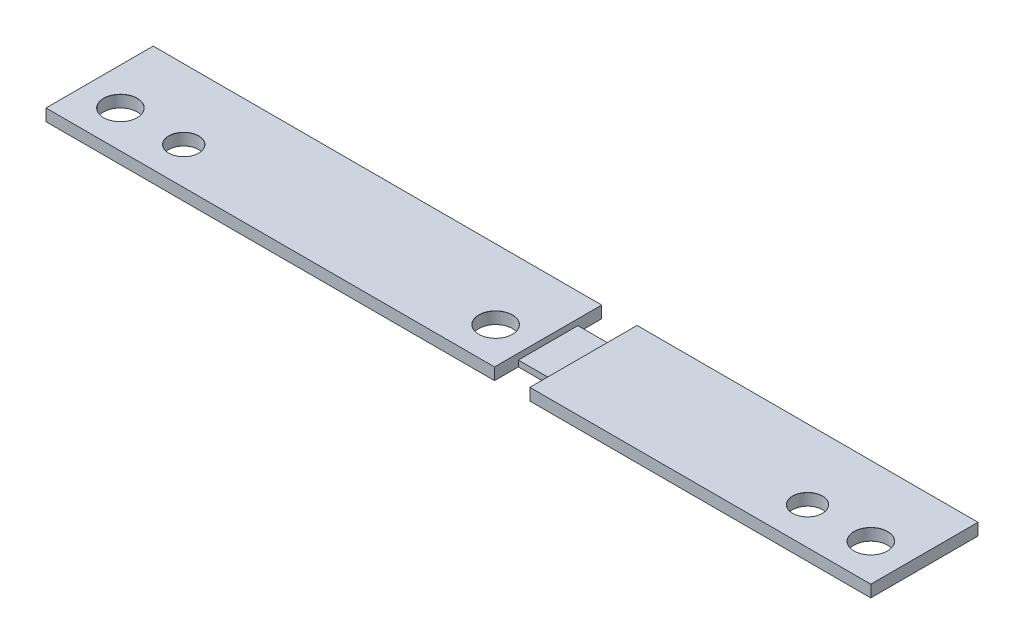
SolidWorks part; units mm, degrees
material "1.2316 (X36CrMo17)"
ref_plane "Front Plane" through (0, 0, 0) normal (0, 0, 1) x (1, 0, 0)
ref_plane "Top Plane" through (0, 0, 0) normal (0, 1, 0) x (1, 0, 0)
ref_plane "Right Plane" through (0, 0, 0) normal (1, 0, 0) x (0, 0, -1)
sketch "Sketch1" plane through (0, 0, 0) normal (0, 1, 0) x (1, 0, 0)
  line L1 (-110.8, 14.4) -> (110.8, 14.4)
  line L2 (-110.8, 14.4) -> (-110.8, -14.4)
  line L3 (-110.8, -14.4) -> (110.8, -14.4)
  line L4 (110.8, 14.4) -> (110.8, -14.4)
  line L5 (-110.8, 14.4) -> (110.8, -14.4) construction
  line L6 (-110.8, -14.4) -> (110.8, 14.4) construction
  point P0 (0, 0)
  dimension "D1" = 221.6
  dimension "D2" = 28.8
extrude "Boss-Extrude1" add sketch "Sketch1" against normal blind 3.2
sketch "Sketch2" plane through (0, 0, 0) normal (0, 1, 0) x (1, 0, 0)
  line L0 (14.45, -14.4) -> (14.45, 14.4) construction
  line L1 (-110.8, -14.4) -> (110.8, -14.4) construction
  line L2 (110.8, 14.4) -> (-110.8, 14.4) construction
  line L4 (-110.8, 14.4) -> (-110.8, -14.4) construction
  line L5 (9.7, 14.4) -> (19.2, 14.4)
  line L6 (9.7, 14.4) -> (9.7, 8)
  line L7 (9.7, 8) -> (19.2, 8)
  line L8 (19.2, 14.4) -> (19.2, 8)
  line L9 (9.7, -14.4) -> (19.2, -14.4)
  line L10 (9.7, -14.4) -> (9.7, -8)
  line L11 (9.7, -8) -> (19.2, -8)
  line L12 (19.2, -14.4) -> (19.2, -8)
  dimension "D1" = 130
  dimension "D2" = 16
  dimension "D3" = 9.5
extrude "Cut-Extrude1" cut sketch "Sketch2" against normal up to next
sketch "Sketch3" plane through (0, 0, 8) normal (0, 0, 1) x (1, 0, 0)
  line L5 (19.2, -3.2) -> (19.2, 0) construction
  line L6 (9.7, 0) -> (19.2, 0)
  line L7 (9.7, 0) -> (9.7, -1.6)
  line L8 (9.7, -1.6) -> (19.2, -1.6)
  line L9 (19.2, 0) -> (19.2, -1.6)
  dimension "D1" = 1.6
extrude "Cut-Extrude2" cut sketch "Sketch3" against normal up to next
sketch "Sketch4" plane through (0, 0, 0) normal (0, 1, 0) x (1, 0, 0)
  point P0 (-100.8, -4.4)
  point P3 (100.8, -4.4)
  point P7 (0, -4.4)
hole_wizard "M8 Clearance Hole1" positions "Sketch4" profile "Sketch5" hole size "M8" standard "ISO" end condition through all
sketch "Sketch5" plane through (-100.8, 0, 4.4) normal (1, 0, 0) x (0, 0, 1)
  line L0 (0, 0) -> (0, 3.2)
  line L1 (0, 3.2) -> (4.525, 3.2)
  line L2 (4.5, 3.175) -> (4.5, 0.025)
  line L3 (4.5, 0.025) -> (4.525, 0)
  line L5 (4.525, 0) -> (0, 0)
  line L6 (-4.5, 0.025) -> (-4.525, 0) construction
  line L7 (4.525, 3.2) -> (4.5, 3.175)
  line L8 (-4.525, 3.2) -> (-4.5, 3.175) construction
  line L11 (0, -6.35) -> (0, 107.95) construction
  dimension "Thru Hole Dia." = 9
  dimension "Thru Hole Depth" = 3.2
  dimension "Near C'Sink Dia." = 9.05
  dimension "Near C'Sink Angle" = 90
  dimension "Far C'Sink Dia." = 9.05
  dimension "Far C'Sink Angle" = 90
sketch "Sketch6" plane through (0, 0, 0) normal (0, 1, 0) x (1, 0, 0)
  point P0 (83.8, -4.4)
  point P3 (-83.8, -4.4)
hole_wizard "Ø8.0mm Dowel Hole1" positions "Sketch6" profile "Sketch7" hole size "Ø8.0" standard "ISO" end condition through all
sketch "Sketch7" plane through (83.8, 0, 4.4) normal (1, 0, 0) x (0, 0, 1)
  line L0 (0, 0) -> (0, 3.2)
  line L1 (0, 3.2) -> (4.025, 3.2)
  line L2 (4, 3.175) -> (4, 0.025)
  line L3 (4, 0.025) -> (4.025, 0)
  line L5 (4.025, 0) -> (0, 0)
  line L6 (-4, 0.025) -> (-4.025, 0) construction
  line L7 (4.025, 3.2) -> (4, 3.175)
  line L8 (-4.025, 3.2) -> (-4, 3.175) construction
  line L11 (0, -6.35) -> (0, 107.95) construction
  dimension "Thru Hole Dia." = 8
  dimension "Thru Hole Depth" = 3.2
  dimension "Near C'Sink Dia." = 8.05
  dimension "Near C'Sink Angle" = 90
  dimension "Far C'Sink Dia." = 8.05
  dimension "Far C'Sink Angle" = 90
